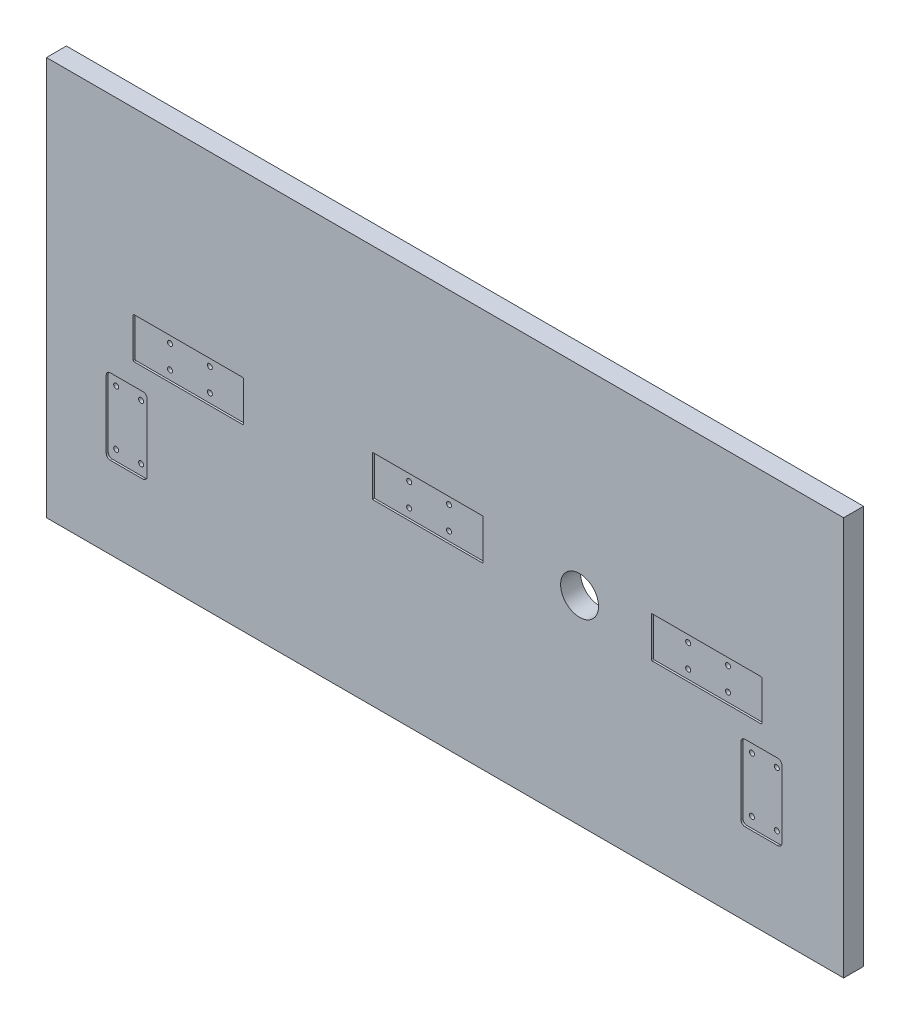
SolidWorks part; units mm, degrees
ref_plane "정면" through (0, 0, 0) normal (0, 0, 1) x (1, 0, 0)
ref_plane "윗면" through (0, 0, 0) normal (0, 1, 0) x (1, 0, 0)
ref_plane "우측면" through (0, 0, 0) normal (1, 0, 0) x (0, 0, -1)
sketch "스케치1" plane through (0, 0, 0) normal (0, 0, 1) x (1, 0, 0)
  line L1 (0, 0) -> (800, 0)
  line L2 (0, 0) -> (0, 400)
  line L3 (0, 400) -> (800, 400)
  line L4 (800, 0) -> (800, 400)
  dimension "D1" = 800
  dimension "D2" = 400
extrude "보스-돌출1" add sketch "스케치1" along normal blind 20
sketch "스케치2" plane through (0, 0, 20) normal (0, 0, 1) x (1, 0, 0)
  line L0 (0, 400) -> (0, 0) construction
  line L1 (64, 158) -> (97, 158)
  line L2 (60, 154) -> (60, 86)
  line L3 (64, 82) -> (97, 82)
  line L4 (101, 154) -> (101, 86)
  line L5 (88, 220.5) -> (197, 220.5)
  line L6 (87, 219.5) -> (87, 180.5)
  line L7 (88, 179.5) -> (197, 179.5)
  line L8 (198, 219.5) -> (198, 180.5)
  line L9 (327, 220.5) -> (438, 220.5)
  line L10 (327, 220.5) -> (327, 179.5)
  line L11 (327, 179.5) -> (438, 179.5)
  line L12 (438, 220.5) -> (438, 179.5)
  line L13 (608, 220.5) -> (717, 220.5)
  line L14 (607, 219.5) -> (607, 180.5)
  line L15 (608, 179.5) -> (717, 179.5)
  line L16 (718, 219.5) -> (718, 180.5)
  line L17 (87, 200) -> (718, 200) construction
  line L18 (701, 158) -> (734, 158)
  line L19 (697, 154) -> (697, 86)
  line L20 (701, 82) -> (734, 82)
  line L21 (738, 154) -> (738, 86)
  line L23 (800, 0) -> (800, 400) construction
  line L24 (800, 400) -> (0, 400) construction
  arc A0 (697, 86) -> (701, 82) centre (701, 86) ccw
  arc A1 (734, 82) -> (738, 86) centre (734, 86) ccw
  arc A2 (734, 158) -> (738, 154) centre (734, 154) cw
  arc A3 (701, 158) -> (697, 154) centre (701, 154) ccw
  arc A4 (60, 86) -> (64, 82) centre (64, 86) ccw
  arc A5 (97, 82) -> (101, 86) centre (97, 86) ccw
  arc A6 (97, 158) -> (101, 154) centre (97, 154) cw
  arc A7 (64, 158) -> (60, 154) centre (64, 154) ccw
  arc A8 (608, 220.5) -> (607, 219.5) centre (608, 219.5) ccw
  arc A9 (717, 220.5) -> (718, 219.5) centre (717, 219.5) cw
  arc A10 (717, 179.5) -> (718, 180.5) centre (717, 180.5) ccw
  arc A11 (607, 180.5) -> (608, 179.5) centre (608, 180.5) ccw
  arc A12 (197, 179.5) -> (198, 180.5) centre (197, 180.5) ccw
  arc A13 (197, 220.5) -> (198, 219.5) centre (197, 219.5) cw
  arc A14 (87, 180.5) -> (88, 179.5) centre (88, 180.5) ccw
  arc A15 (88, 220.5) -> (87, 219.5) centre (88, 219.5) ccw
  point P38 (60, 82)
  point P45 (60, 158)
  point P52 (718, 179.5)
  point P55 (607, 179.5)
  point P62 (87, 179.5)
  point P65 (87, 220.5)
  dimension "D15" = 4
  dimension "D16" = 1
  dimension "D17" = 1
  dimension "D18" = 1
  dimension "D19" = 1
  dimension "D20" = 1
  dimension "D1" = 60
  dimension "D2" = 41
  dimension "D3" = 111
  dimension "D4" = 82
  dimension "D5" = 129
  dimension "D6" = 111
  dimension "D7" = 169
  dimension "D8" = 111
  dimension "D9" = 41
  dimension "D10" = 200
  dimension "D11" = 242
  dimension "D12" = 76
  dimension "D13" = 41
  dimension "D14" = 62
extrude "컷-돌출1" cut sketch "스케치2" against normal blind 2
sketch "스케치7" plane through (0, 0, 18) normal (0, 0, 1) x (1, 0, 0)
  line L1 (0, 400) -> (0, 0) construction
  line L2 (197, 220.5) -> (88, 220.5) construction
  line L3 (800, 0) -> (800, 400) construction
  line L4 (64, 82) -> (97, 82) construction
  line L5 (97, 158) -> (64, 158) construction
  line L8 (88, 179.5) -> (197, 179.5) construction
  point P0 (68, 147.5)
  point P1 (93, 147.5)
  point P2 (68, 92.5)
  point P3 (93, 92.5)
  point P4 (122, 211.5)
  point P5 (122, 188.5)
  point P6 (162, 211.5)
  point P7 (162, 188.5)
  point P8 (362, 211.5)
  point P9 (362, 188.5)
  point P10 (402, 211.5)
  point P11 (402, 188.5)
  point P12 (642, 211.5)
  point P13 (642, 188.5)
  point P14 (682, 211.5)
  point P15 (682, 188.5)
  point P16 (706, 147.5)
  point P17 (731, 147.5)
  point P18 (706, 92.5)
  point P19 (731, 92.5)
  dimension "D2" = 9
  dimension "D3" = 118
  dimension "D4" = 40
  dimension "D5" = 200
  dimension "D6" = 40
  dimension "D7" = 240
  dimension "D8" = 40
  dimension "D9" = 25
  dimension "D10" = 68
  dimension "D11" = 613
  dimension "D12" = 25
  dimension "D13" = 10.5
  dimension "D14" = 10.5
  dimension "D15" = 9
sketch "스케치10" plane through (0, 0, 18) normal (0, 0, 1) x (1, 0, 0)
  point P0 (162, 188.5)
  point P3 (162, 211.5)
  point P6 (122, 211.5)
  point P9 (122, 188.5)
  point P12 (93, 92.5)
  point P15 (68, 92.5)
  point P18 (68, 147.5)
  point P21 (93, 147.5)
  point P24 (362, 211.5)
  point P27 (402, 211.5)
  point P30 (402, 188.5)
  point P33 (362, 188.5)
  point P36 (642, 211.5)
  point P39 (682, 211.5)
  point P42 (682, 188.5)
  point P45 (642, 188.5)
  point P48 (706, 92.5)
  point P51 (731, 92.5)
  point P54 (731, 147.5)
  point P57 (706, 147.5)
hole_wizard "M6 나사 구멍2" positions "스케치10" profile "스케치9" tap size "M6" standard "ISO"
sketch "스케치9" plane through (162, 188.5, 18) normal (1, 0, 0) x (0, -1, 0)
  line L0 (0, 0) -> (0, 12.5022)
  line L1 (0, 12.5022) -> (2.5, 11)
  line L2 (2.5, 11) -> (2.5, 0)
  line L5 (2.5, 0) -> (0, 0)
  line L10 (0, 12.5022) -> (-2.5, 11) construction
  line L11 (0, -6.35) -> (0, 107.95) construction
  dimension "탭 드릴 지름" = 5
  dimension "탭 드릴 깊이" = 11
  dimension "드릴 각도" = 118
cosmetic thread "구멍 나사산1" parameters "D1"=6, "D2"=6
cosmetic thread "구멍 나사산2" parameters "D1"=6, "D2"=6
cosmetic thread "구멍 나사산3" parameters "D1"=6, "D2"=6
cosmetic thread "구멍 나사산4" parameters "D1"=6, "D2"=6
cosmetic thread "구멍 나사산7" parameters "D1"=6, "D2"=6
cosmetic thread "구멍 나사산8" parameters "D1"=6, "D2"=6
cosmetic thread "구멍 나사산11" parameters "D1"=6, "D2"=6
cosmetic thread "구멍 나사산12" parameters "D1"=6, "D2"=6
cosmetic thread "구멍 나사산13" parameters "D1"=6, "D2"=6
cosmetic thread "구멍 나사산14" parameters "D1"=6, "D2"=6
cosmetic thread "구멍 나사산15" parameters "D1"=6, "D2"=6
cosmetic thread "구멍 나사산16" parameters "D1"=6, "D2"=6
cosmetic thread "구멍 나사산18" parameters "D1"=6, "D2"=6
cosmetic thread "구멍 나사산19" parameters "D1"=6, "D2"=6
cosmetic thread "구멍 나사산37" parameters "D1"=6, "D2"=6
cosmetic thread "구멍 나사산38" parameters "D1"=6, "D2"=6
cosmetic thread "구멍 나사산39" parameters "D1"=6, "D2"=6
cosmetic thread "구멍 나사산40" parameters "D1"=6, "D2"=6
cosmetic thread "구멍 나사산41" parameters "D1"=6, "D2"=6
cosmetic thread "구멍 나사산42" parameters "D1"=6, "D2"=6
sketch "스케치11" plane through (0, 0, 20) normal (0, 0, 1) x (1, 0, 0)
  line L0 (800, 400) -> (0, 400) construction
  line L2 (800, 0) -> (800, 400) construction
  circle A0 centre (535, 200) radius 19.05
  dimension "D2" = 38.1
  dimension "D1" = 200
  dimension "D3" = 265
extrude "컷-돌출2" cut sketch "스케치11" against normal through all
sketch "스케치12" plane through (0, 0, 0) normal (0, 0, -1) x (-1, 0, 0)
  line L0 (0, 0) -> (-800, 0) construction
  line L1 (0, 400) -> (0, 0) construction
  point P0 (-30, 10)
  point P1 (-70, 10)
  point P2 (-30, 50)
  point P3 (-70, 50)
  point P4 (-730, 10)
  point P5 (-770, 10)
  point P6 (-730, 50)
  point P7 (-770, 50)
  point P8 (-730, 390)
  point P9 (-770, 390)
  point P10 (-730, 350)
  point P11 (-770, 350)
  point P12 (-30, 390)
  point P13 (-70, 390)
  point P14 (-30, 350)
  point P15 (-70, 350)
  dimension "D1" = 10
  dimension "D2" = 30
  dimension "D3" = 40
  dimension "D4" = 40
  dimension "D5" = 300
  dimension "D6" = 40
  dimension "D7" = 40
  dimension "D8" = 660
hole_wizard "M6 나사 구멍3" positions "스케치12" profile "스케치13" tap size "M6" standard "ISO"
sketch "스케치13" plane through (30, 10, 0) normal (1, 0, 0) x (0, 1, 0)
  line L0 (0, 0) -> (0, 14.5022)
  line L1 (0, 14.5022) -> (2.5, 13)
  line L2 (2.5, 13) -> (2.5, 0)
  line L5 (2.5, 0) -> (0, 0)
  line L10 (0, 14.5022) -> (-2.5, 13) construction
  line L11 (0, -6.35) -> (0, 107.95) construction
  dimension "탭 드릴 지름" = 5
  dimension "탭 드릴 깊이" = 13
  dimension "드릴 각도" = 118
cosmetic thread "구멍 나사산21" parameters "D1"=8, "D2"=6
cosmetic thread "구멍 나사산22" parameters "D1"=8, "D2"=6
cosmetic thread "구멍 나사산23" parameters "D1"=8, "D2"=6
cosmetic thread "구멍 나사산24" parameters "D1"=8, "D2"=6
cosmetic thread "구멍 나사산25" parameters "D1"=8, "D2"=6
cosmetic thread "구멍 나사산26" parameters "D1"=8, "D2"=6
cosmetic thread "구멍 나사산27" parameters "D1"=8, "D2"=6
cosmetic thread "구멍 나사산28" parameters "D1"=8, "D2"=6
cosmetic thread "구멍 나사산29" parameters "D1"=8, "D2"=6
cosmetic thread "구멍 나사산30" parameters "D1"=8, "D2"=6
cosmetic thread "구멍 나사산31" parameters "D1"=8, "D2"=6
cosmetic thread "구멍 나사산32" parameters "D1"=8, "D2"=6
cosmetic thread "구멍 나사산33" parameters "D1"=8, "D2"=6
cosmetic thread "구멍 나사산34" parameters "D1"=8, "D2"=6
cosmetic thread "구멍 나사산35" parameters "D1"=8, "D2"=6
cosmetic thread "구멍 나사산36" parameters "D1"=8, "D2"=6
